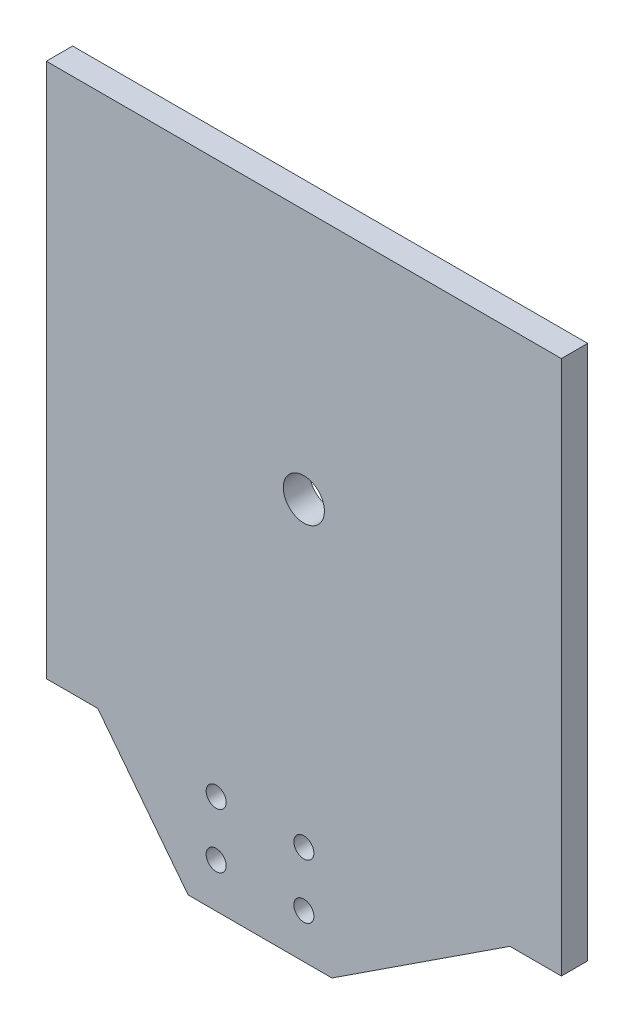
SolidWorks part; units mm, degrees
ref_plane "Front Plane" through (0, 0, 0) normal (0, 0, 1) x (1, 0, 0)
ref_plane "Top Plane" through (0, 0, 0) normal (0, 1, 0) x (1, 0, 0)
ref_plane "Right Plane" through (0, 0, 0) normal (1, 0, 0) x (0, 0, -1)
sketch "Sketch1" plane through (0, 0, 0) normal (0, 0, 1) x (1, 0, 0)
  line L0 (0, 58.1025) -> (119.38, 58.1025) construction
  line L1 (0, 0) -> (119.38, 0) construction
  line L2 (0, 0) -> (0, 116.205)
  line L3 (0, 116.205) -> (119.38, 116.205)
  line L4 (119.38, 0) -> (119.38, 116.205)
  line L5 (0, 0) -> (0, -7.747)
  line L6 (0, -7.747) -> (11.938, -7.747)
  line L7 (11.938, -7.747) -> (32.8612, -34.7218)
  line L8 (32.8612, -34.7218) -> (66.1987, -34.7218)
  line L9 (66.1987, -34.7218) -> (107.442, -7.747)
  line L10 (107.442, -7.747) -> (119.38, -7.747)
  line L11 (119.38, -7.747) -> (119.38, 0)
  line L12 (59.69, 58.1025) -> (59.69, -24.4475) construction
  line L13 (39.37, -11.7475) -> (59.69, -11.7475) construction
  line L14 (39.37, -11.7475) -> (39.37, -24.4475) construction
  line L15 (39.37, -24.4475) -> (59.69, -24.4475) construction
  line L16 (59.69, -11.7475) -> (59.69, -24.4475) construction
  line L17 (49.53, -11.7475) -> (49.53, -24.4475) construction
  line L18 (49.53, -24.4475) -> (49.53, -34.7218) construction
  circle A0 centre (59.69, 58.1025) radius 4.7625
  circle A1 centre (39.37, -11.7475) radius 2.3241
  circle A2 centre (59.69, -11.7475) radius 2.3241
  circle A3 centre (59.69, -24.4475) radius 2.3241
  circle A4 centre (39.37, -24.4475) radius 2.3241
  point P9 (59.69, 58.1025)
  dimension "D2" = 9.525
  dimension "D3" = 4.6482
  dimension "D4" = 20.32
  dimension "D5" = 12.7
  dimension "D6" = 26.9748
  dimension "D1" = 119.38
  dimension "D7" = 69.85
  dimension "D8" = 116.205
  dimension "D9" = 7.747
  dimension "D10" = 33.3375
  dimension "D11" = 11.938
extrude "Boss-Extrude1" add sketch "Sketch1" along normal blind 6.096
